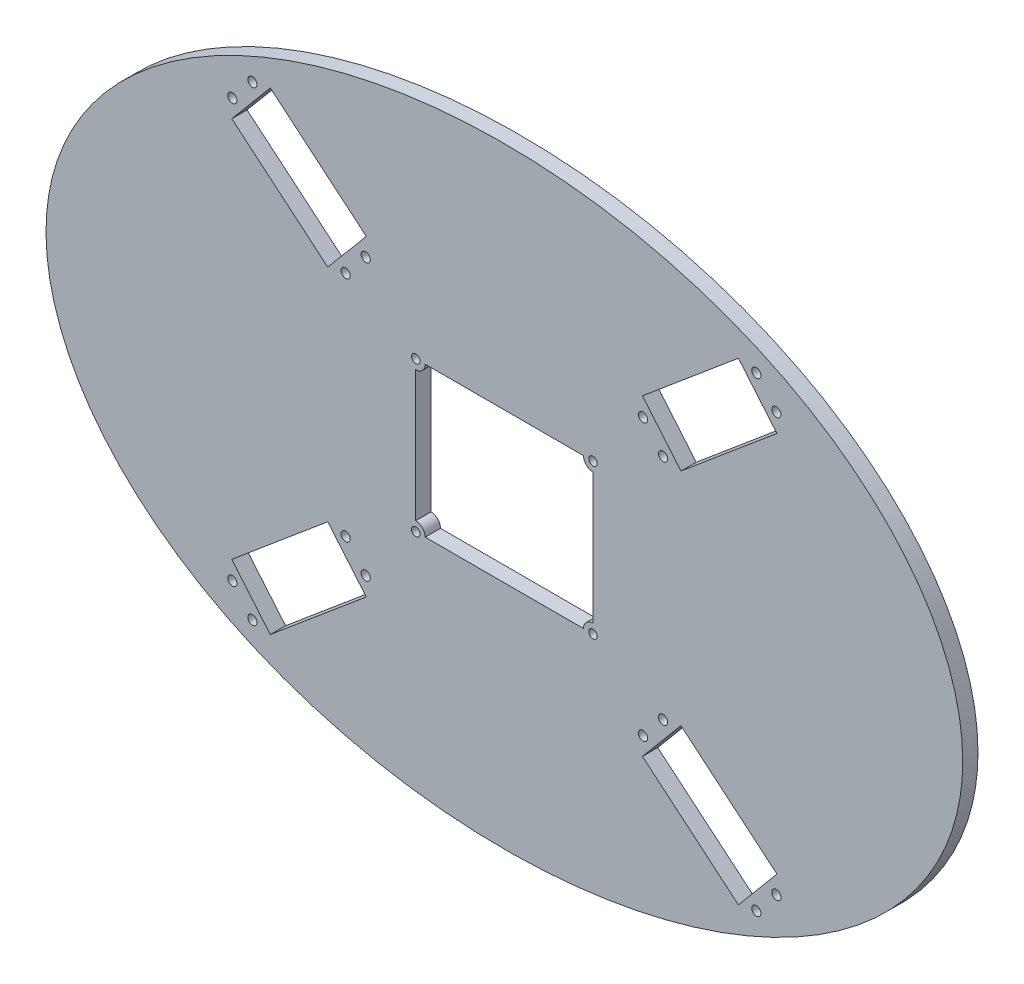
SolidWorks part; units mm, degrees
material "Plain Carbon Steel"
ref_plane "Front" through (0, 0, 0) normal (0, 0, 1) x (1, 0, 0)
ref_plane "Top" through (0, 0, 0) normal (0, 1, 0) x (1, 0, 0)
ref_plane "Right" through (0, 0, 0) normal (1, 0, 0) x (0, 0, -1)
ref_plane "Plane1" through (0, 0, 5) normal (0, 0, 1) x (1, 0, 0)
sketch "Sketch1" plane through (0, 0, 5) normal (0, 0, 1) x (1, 0, 0)
  ellipse E0 centre (0, 0) end of major axis (150, 0) minor radius 100
  point P0 (0, 0)
  point P1 (150, 0)
  point P2 (0, -100)
extrude "Boss-Extrude1" add sketch "Sketch1" against normal blind 5
sketch "Sketch2" plane through (0, 0, 0) normal (0, 0, -1) x (-1, 0, 0)
  line L0 (25.9, 24.5) -> (-25.9, 24.5)
  line L1 (-29, 21.4) -> (-29, -21.4)
  line L2 (-25.9, -24.5) -> (25.9, -24.5)
  line L3 (29, -21.4) -> (29, 21.4)
  arc A0 (29, 21.4) -> (25.9, 24.5) centre (29, 24.5) cw
  arc A1 (-25.9, 24.5) -> (-29, 21.4) centre (-29, 24.5) cw
  arc A2 (-29, -21.4) -> (-25.9, -24.5) centre (-29, -24.5) cw
  arc A3 (25.9, -24.5) -> (29, -21.4) centre (29, -24.5) cw
extrude "Cut-Extrude1" cut sketch "Sketch2" against normal through all
sketch "Sketch3" plane through (0, 0, 5) normal (0, 0, 1) x (1, 0, 0)
  circle A0 centre (29, 24.5) radius 3.1
sketch "Sketch4" plane through (0, 0, 5) normal (0, 0, 1) x (1, 0, 0)
  circle A0 centre (29, -24.5) radius 3.1
sketch "Sketch5" plane through (0, 0, 5) normal (0, 0, 1) x (1, 0, 0)
  circle A0 centre (-29, -24.5) radius 3.1
sketch "Sketch6" plane through (0, 0, 5) normal (0, 0, 1) x (1, 0, 0)
  circle A0 centre (-29, 24.5) radius 3.1
sketch "Sketch7" plane through (0, 0, 5) normal (0, 0, 1) x (1, 0, 0)
  line L0 (45.1915, -51.098) -> (76.5993, -77.4523)
  line L1 (76.5993, -77.4523) -> (89.1979, -62.4378)
  line L2 (89.1979, -62.4378) -> (57.7901, -36.0835)
  line L3 (57.7901, -36.0835) -> (45.1915, -51.098)
extrude "Cut-Extrude2" cut sketch "Sketch7" against normal through all
sketch "Sketch8" plane through (0, 0, 5) normal (0, 0, 1) x (1, 0, 0)
  line L0 (-76.5987, -77.4518) -> (-45.1909, -51.0975)
  line L1 (-45.1909, -51.0975) -> (-57.7895, -36.083)
  line L2 (-57.7895, -36.083) -> (-89.1973, -62.4373)
  line L3 (-89.1973, -62.4373) -> (-76.5987, -77.4518)
extrude "Cut-Extrude3" cut sketch "Sketch8" against normal through all
sketch "Sketch9" plane through (0, 0, 5) normal (0, 0, 1) x (1, 0, 0)
  line L0 (-45.1917, 51.0983) -> (-76.5995, 77.4526)
  line L1 (-76.5995, 77.4526) -> (-89.1981, 62.4382)
  line L2 (-89.1981, 62.4382) -> (-57.7903, 36.0839)
  line L3 (-57.7903, 36.0839) -> (-45.1917, 51.0983)
extrude "Cut-Extrude4" cut sketch "Sketch9" against normal through all
sketch "Sketch10" plane through (0, 0, 0) normal (0, 0, -1) x (-1, 0, 0)
  line L0 (-89.198, 62.4374) -> (-57.7902, 36.0831)
  line L1 (-57.7902, 36.0831) -> (-45.1916, 51.0975)
  line L2 (-45.1916, 51.0975) -> (-76.5994, 77.4518)
  line L3 (-76.5994, 77.4518) -> (-89.198, 62.4374)
extrude "Cut-Extrude5" cut sketch "Sketch10" against normal through all
ref_plane "Plane2" through (0, -24.5, 0) normal (0, 1, 0) x (1, 0, 0)
sketch "Sketch11" plane through (0, -24.5, 0) normal (0, 1, 0) x (1, 0, 0)
  line L0 (30.375, 0) -> (29, 0)
  line L1 (29, 0) -> (29, -12.5)
  line L2 (29, -12.5) -> (30.375, -12.5)
  line L3 (30.375, -12.5) -> (30.375, 0)
  line L4 (29, 0) -> (29, -12.5) construction
revolve "Cut-Revolve1" cut sketch "Sketch11" angle 360 about L4
ref_plane "Plane3" through (0, 24.5, 0) normal (0, 1, 0) x (1, 0, 0)
sketch "Sketch12" plane through (0, 24.5, 0) normal (0, 1, 0) x (1, 0, 0)
  line L0 (30.375, 0) -> (29, 0)
  line L1 (29, 0) -> (29, -12.5)
  line L2 (29, -12.5) -> (30.375, -12.5)
  line L3 (30.375, -12.5) -> (30.375, 0)
  line L4 (29, 0) -> (29, -12.5) construction
revolve "Cut-Revolve2" cut sketch "Sketch12" angle 360 about L4
sketch "Sketch13" plane through (0, 24.5, 0) normal (0, 1, 0) x (1, 0, 0)
  line L0 (-27.625, 0) -> (-29, 0)
  line L1 (-29, 0) -> (-29, -12.5)
  line L2 (-29, -12.5) -> (-27.625, -12.5)
  line L3 (-27.625, -12.5) -> (-27.625, 0)
  line L4 (-29, 0) -> (-29, -12.5) construction
revolve "Cut-Revolve3" cut sketch "Sketch13" angle 360 about L4
sketch "Sketch14" plane through (0, -24.5, 0) normal (0, 1, 0) x (1, 0, 0)
  line L0 (-27.625, 0) -> (-29, 0)
  line L1 (-29, 0) -> (-29, -12.5)
  line L2 (-29, -12.5) -> (-27.625, -12.5)
  line L3 (-27.625, -12.5) -> (-27.625, 0)
  line L4 (-29, 0) -> (-29, -12.5) construction
revolve "Cut-Revolve4" cut sketch "Sketch14" angle 360 about L4
hole_wizard "Ø3.0 (3) Diameter Hole1" positions "Sketch16" profile "Sketch15" hole size "Ø3.0" standard "ANSI Metric"
sketch "Sketch16" plane through (0, 0, 5) normal (0, 0, 1) x (1, 0, 0)
  point P0 (82.4548, -76.2302)
  point P1 (89.0112, -68.4165)
  point P2 (45.3782, -45.1193)
  point P3 (-45.3784, 45.1196)
  point P4 (-45.3776, -45.1188)
  point P5 (-51.9341, -37.3051)
  point P6 (-82.4542, -76.2297)
  point P7 (-89.0106, -68.416)
  point P8 (51.9347, -37.3056)
  point P9 (51.9348, 37.3052)
  point P10 (45.3783, 45.1188)
  point P11 (82.4549, 76.2297)
  point P12 (-51.9348, 37.306)
  point P13 (-82.455, 76.2305)
  point P14 (-89.0114, 68.4169)
  point P15 (89.0113, 68.4161)
sketch "Sketch15" plane through (82.4548, -76.2302, 5) normal (1, 0, 0) x (0, -1, 0)
  line L0 (0, 0) -> (0, 5)
  line L1 (0, 5) -> (1.5, 5)
  line L2 (1.5, 5) -> (1.5, 0)
  line L5 (1.5, 0) -> (0, 0)
  line L11 (0, -6.35) -> (0, 107.95) construction
  dimension "Thru Hole Dia." = 3
  dimension "Thru Hole Depth" = 5
